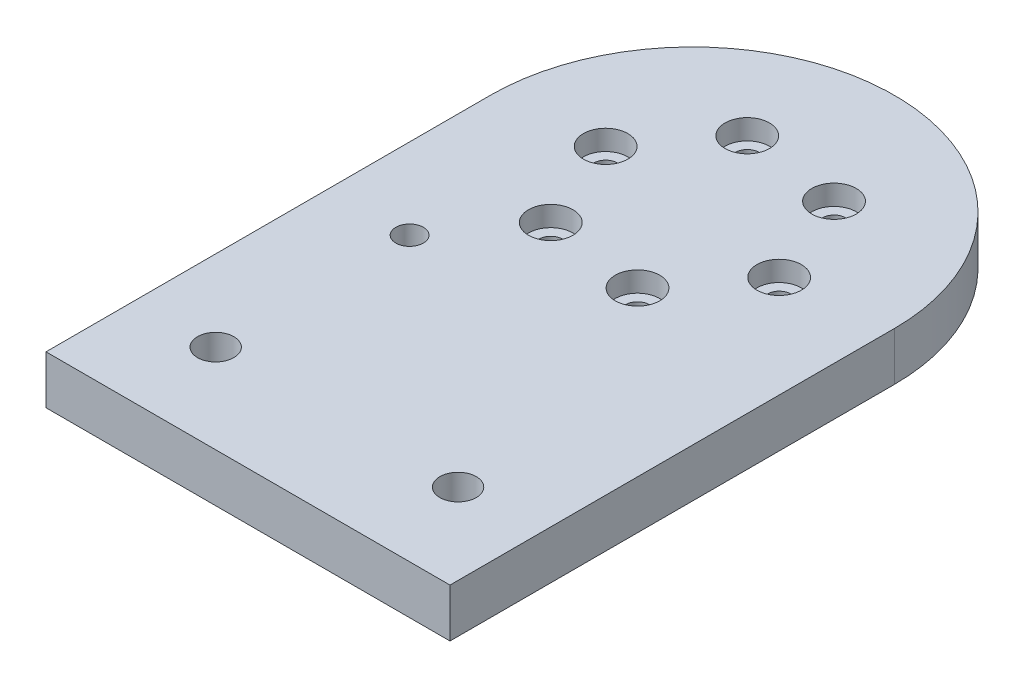
SolidWorks part; units mm, degrees
material "Aleación 6061"
ref_plane "Alzado" through (0, 0, 0) normal (0, 0, 1) x (1, 0, 0)
ref_plane "Planta" through (0, 0, 0) normal (0, 1, 0) x (1, 0, 0)
ref_plane "Vista lateral" through (0, 0, 0) normal (1, 0, 0) x (0, 0, -1)
sketch "Sk_Placa" plane through (0, 0, 0) normal (0, 1, 0) x (1, 0, 0)
  line L1 (-25, -526) -> (25, -526)
  line L2 (-25, -526) -> (-25, -490)
  line L3 (-25, -490) -> (25, -490)
  line L4 (25, -526) -> (25, -490)
  line L5 (-25, -526) -> (25, -490) construction
  line L6 (-25, -490) -> (25, -526) construction
  point P0 (0, -508)
  dimension "D1" = 50
  dimension "D2" = 36
  dimension "D3" = 508
extrude "Placa" add sketch "Sk_Placa" along normal blind 6 from offset 34.5
sketch "Sk_Extremo" plane through (0, 0, 0) normal (0, 1, 0) x (1, 0, 0)
  circle A0 centre (0, -490) radius 25
  dimension "D1" = 50
  dimension "D2" = 490
extrude "Extremo" add sketch "Sk_Extremo" along normal blind 6 from offset 34.5
sketch "Sk_Pasantes_M2-5_cubo_J5" plane through (0, 0, 0) normal (0, 1, 0) x (1, 0, 0)
  circle A0 centre (12.3902, -491.6532) radius 1.45
  circle A1 centre (4.7634, -501.5568) radius 1.45
  circle A2 centre (-7.6268, -499.9036) radius 1.45
  circle A3 centre (-12.3902, -488.3468) radius 1.45
  circle A4 centre (-4.7634, -478.4432) radius 1.45
  circle A5 centre (7.6268, -480.0964) radius 1.45
  dimension "D1" = 2.9
  dimension "D4" = 2.9
  dimension "D7" = 2.9
  dimension "D10" = 2.9
  dimension "D13" = 2.9
  dimension "D16" = 2.9
  dimension "D2" = 12.3902
  dimension "D3" = 491.6532
  dimension "D5" = 4.7634
  dimension "D6" = 501.5568
  dimension "D8" = 7.6268
  dimension "D9" = 499.9036
  dimension "D11" = 12.3902
  dimension "D12" = 488.3468
  dimension "D14" = 4.7634
  dimension "D15" = 478.4432
  dimension "D17" = 7.6268
  dimension "D18" = 480.0964
extrude "Pasantes_M2-5_cubo_J5" cut sketch "Sk_Pasantes_M2-5_cubo_J5" along normal blind 6 from offset 34.5
sketch "Sk_Cajas_M2-5_J5" plane through (0, 0, 0) normal (0, 1, 0) x (1, 0, 0)
  circle A0 centre (12.3902, -491.6532) radius 2.75
  circle A1 centre (4.7634, -501.5568) radius 2.75
  circle A2 centre (-7.6268, -499.9036) radius 2.75
  circle A3 centre (-12.3902, -488.3468) radius 2.75
  circle A4 centre (-4.7634, -478.4432) radius 2.75
  circle A5 centre (7.6268, -480.0964) radius 2.75
  dimension "D1" = 5.5
  dimension "D4" = 5.5
  dimension "D7" = 5.5
  dimension "D10" = 5.5
  dimension "D13" = 5.5
  dimension "D16" = 5.5
  dimension "D2" = 12.3902
  dimension "D3" = 491.6532
  dimension "D5" = 4.7634
  dimension "D6" = 501.5568
  dimension "D8" = 7.6268
  dimension "D9" = 499.9036
  dimension "D11" = 12.3902
  dimension "D12" = 488.3468
  dimension "D14" = 4.7634
  dimension "D15" = 478.4432
  dimension "D17" = 7.6268
  dimension "D18" = 480.0964
extrude "Cajas_M2-5_J5" cut sketch "Sk_Cajas_M2-5_J5" along normal blind 2.5 from offset 38
sketch "Sk_Extension_pestanas" plane through (0, 0, 0) normal (0, 1, 0) x (1, 0, 0)
  line L1 (-25, -545) -> (25, -545)
  line L2 (-25, -545) -> (-25, -526)
  line L3 (-25, -526) -> (25, -526)
  line L4 (25, -545) -> (25, -526)
  line L5 (-25, -545) -> (25, -526) construction
  line L6 (-25, -526) -> (25, -545) construction
  point P0 (0, -535.5)
  dimension "D1" = 50
  dimension "D2" = 19
  dimension "D3" = 535.5
extrude "Extension_pestanas" add sketch "Sk_Extension_pestanas" along normal blind 6 from offset 34.5
sketch "Sk_Pasantes_M4_repisa" plane through (0, 0, 0) normal (0, 1, 0) x (1, 0, 0)
  circle A0 centre (-15, -534) radius 2.25
  circle A1 centre (15, -534) radius 2.25
  dimension "D1" = 4.5
  dimension "D4" = 4.5
  dimension "D2" = 15
  dimension "D3" = 534
  dimension "D5" = 15
  dimension "D6" = 534
extrude "Pasantes_M4_repisa" cut sketch "Sk_Pasantes_M4_repisa" along normal blind 6 from offset 34.5
sketch "Sk_Pasante_M3_cincho" plane through (0, 0, 0) normal (0, 1, 0) x (1, 0, 0)
  circle A0 centre (-15, -510) radius 1.7
  dimension "D1" = 3.4
  dimension "D2" = 15
  dimension "D3" = 510
extrude "Pasante_M3_cincho" cut sketch "Sk_Pasante_M3_cincho" along normal blind 6 from offset 34.5
